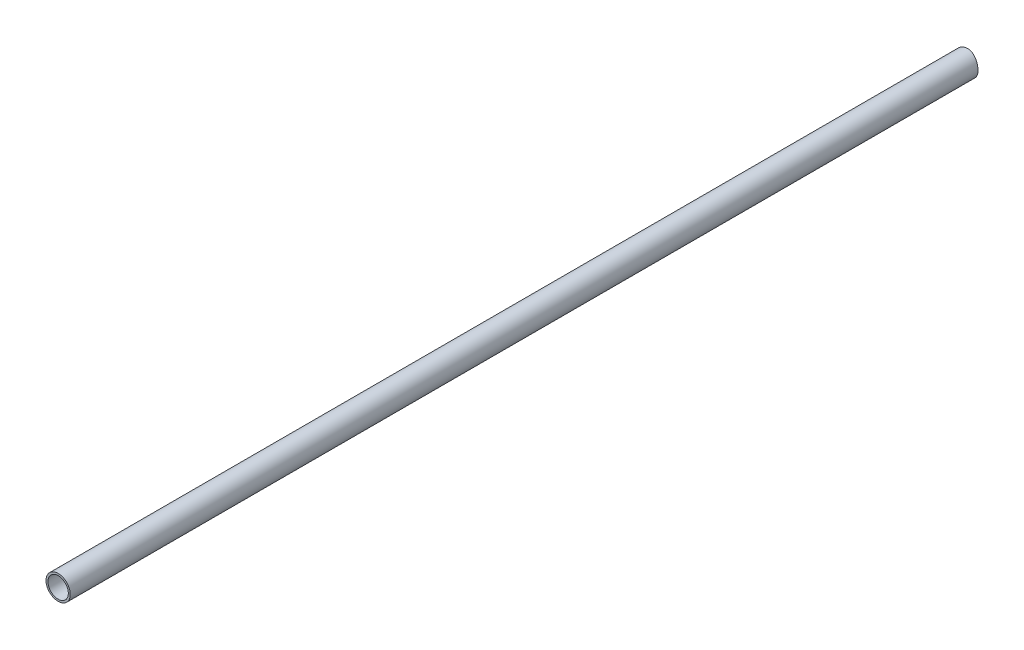
SolidWorks part; units mm, degrees
material "ASTM A36 Steel"
ref_plane "Front Plane" through (0, 0, 0) normal (0, 0, 1) x (1, 0, 0)
ref_plane "Top Plane" through (0, 0, 0) normal (0, 1, 0) x (1, 0, 0)
ref_plane "Right Plane" through (0, 0, 0) normal (1, 0, 0) x (0, 0, -1)
sketch "Sketch1" plane through (0, 0, 0) normal (0, 0, 1) x (1, 0, 0)
  circle A0 centre (0, 0) radius 13.35
  circle A1 centre (0, 0) radius 11.24
  dimension "D1" = 26.7
  dimension "D2" = 2.11
extrude "Boss-Extrude1" add sketch "Sketch1" along normal blind 1100
sketch "Sketch2" plane through (0, 0, 0) normal (1, 0, 0) x (0, 0, -1)
  circle A0 centre (0, 0) radius 50
  dimension "D1" = 100
extrude "Cut-Extrude1" cut sketch "Sketch2" against normal through all both and the other way through all
sketch "Sketch3" plane through (0, 0, 0) normal (1, 0, 0) x (0, 0, -1)
  circle A0 centre (0, 0) radius 1050
  circle A1 centre (0, 0) radius 2231.3625
  dimension "D1" = 2100
extrude "Cut-Extrude2" cut sketch "Sketch3" against normal through all both and the other way through all
